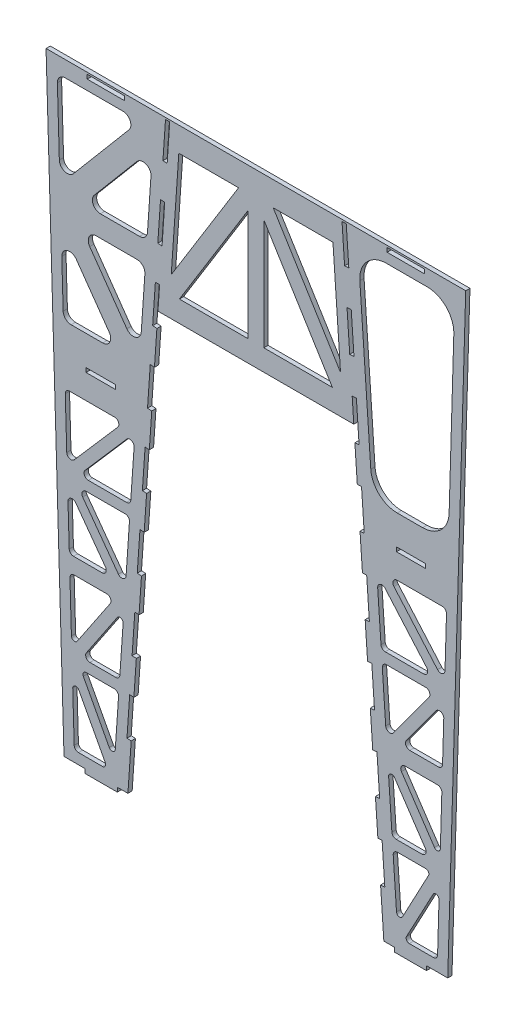
SolidWorks part; units mm, degrees
ref_plane "Front Plane" through (0, 0, 0) normal (0, 0, 1) x (1, 0, 0)
ref_plane "Top Plane" through (0, 0, 0) normal (0, 1, 0) x (1, 0, 0)
ref_plane "Right Plane" through (0, 0, 0) normal (1, 0, 0) x (0, 0, -1)
sketch "Sketch1" plane through (0, 0, 0) normal (0, 0, 1) x (1, 0, 0)
  line L0 (-288.2759, 0) -> (288.2759, 0) construction
  line L1 (-215.8925, 1465.1633) -> (215.8925, 1465.1633)
  line L2 (0, 0) -> (0, 1733.4513) construction
  line L3 (19.05, 1104.9) -> (205.6376, 1104.9)
  line L4 (202.8026, 1145.716) -> (41.4459, 1406.7433)
  line L5 (205.6376, 1104.9) -> (19.05, 1406.7433) construction
  line L6 (205.6376, 1104.9) -> (184.6725, 1406.7433)
  line L7 (183.2417, 1104.9) -> (15.2162, 1376.7154)
  line L8 (19.05, 1406.7433) -> (19.05, 1104.9)
  line L9 (184.6725, 1406.7433) -> (19.05, 1406.7433)
  line L10 (306.6278, 17.4764) -> (234.6272, 1054.1)
  line L12 (459.7218, 17.4764) -> (502.7833, 1465.1633)
  line L13 (459.7218, 7.3164) -> (520.3601, 2060.228) construction
  line L15 (266.6925, 1465.1633) -> (368.5375, 1465.1633)
  line L16 (-237.2124, 1016.8799) -> (-230.6925, 1110.7494) construction
  line L18 (237.2124, 1016.8799) -> (230.6925, 1110.7494) construction
  line L19 (-408.9218, 7.3164) -> (-332.1008, 7.3164)
  line L20 (-502.7833, 1465.1633) -> (-215.8925, 1465.1633)
  line L22 (408.9218, 7.3164) -> (332.7218, 7.3164)
  line L24 (-408.9218, 17.4764) -> (-408.9218, 7.3164) construction
  line L30 (-408.9218, 17.4764) -> (-408.9218, 7.3164)
  line L31 (502.7833, 1465.1633) -> (368.5375, 1465.1633)
  line L32 (-332.1008, 17.4764) -> (-332.1008, 7.3164) construction
  line L33 (-332.1008, 17.4764) -> (-332.1008, 7.3164)
  line L34 (408.9218, 17.4764) -> (408.9218, 7.3164) construction
  line L35 (408.9218, 17.4764) -> (408.9218, 7.3164)
  line L40 (332.7218, 17.4764) -> (332.7218, 7.3164) construction
  line L43 (332.7218, 17.4764) -> (332.7218, 7.3164)
  line L44 (459.7218, 17.4764) -> (408.9218, 17.4764) construction
  line L45 (459.7218, 17.4764) -> (408.9218, 17.4764)
  line L49 (-408.9218, 17.4764) -> (-459.7218, 17.4764)
  line L52 (-332.1008, 17.4764) -> (-306.6278, 17.4764)
  line L53 (332.7218, 17.4764) -> (306.6278, 17.4764)
  line L55 (-459.7218, 17.4764) -> (-502.7833, 1465.1633)
  line L56 (-459.7218, 7.3164) -> (-520.3601, 2060.228) construction
  line L81 (215.8925, 1465.1633) -> (266.6925, 1465.1633)
  line L90 (234.6272, 1054.1) -> (-234.6272, 1054.1)
  line L100 (-234.6272, 1054.1) -> (-306.6278, 17.4764)
  line L124 (-184.6725, 1406.7433) -> (-19.05, 1406.7433)
  line L125 (-19.05, 1406.7433) -> (-19.05, 1104.9)
  line L126 (-183.2417, 1104.9) -> (-15.2162, 1376.7154)
  line L127 (-205.6376, 1104.9) -> (-19.05, 1406.7433) construction
  line L128 (-202.8026, 1145.716) -> (-41.4459, 1406.7433)
  line L129 (-205.6376, 1104.9) -> (-184.6725, 1406.7433)
  line L130 (-19.05, 1104.9) -> (-205.6376, 1104.9)
  point P0 (0, 0)
  point P3 (0, 0)
  point P106 (0, 0)
  point P118 (0, 1054.1)
  dimension "D6" = 25.4
  dimension "D7" = 50.8
  dimension "D8" = 58.42
  dimension "D9" = 19.05
  dimension "D19" = 288.2759
  dimension "D22" = 19.05
  dimension "D23" = 19.05
  dimension "D24" = 1054.1
  dimension "D49" = 50.8
extrude "Boss-Extrude1" add sketch "Sketch1" along normal blind 10.16
fillet "Fillet1" [suppressed] radius 19.05
sketch "Sketch2" plane through (0, 0, 0) normal (0, 0, 1) x (1, 0, 0)
  line L18 (-222.6942, 1372.2749) -> (-212.5765, 1371.5721) construction
  line L56 (-216.5353, 1460.9479) -> (-222.6942, 1372.2749) construction
  line L57 (-212.5765, 1371.5721) -> (-206.3688, 1460.9479) construction
  line L58 (-206.3688, 1460.9479) -> (-216.5353, 1460.9479) construction
  line L59 (-222.6942, 1372.2749) -> (-212.5765, 1371.5721)
  line L61 (-216.5353, 1460.9479) -> (-222.6942, 1372.2749)
  line L63 (-212.5765, 1371.5721) -> (-206.3688, 1460.9479)
  line L176 (-206.3688, 1460.9479) -> (-216.5353, 1460.9479)
  line L181 (-224.8945, 1194.226) -> (-235.0121, 1194.9287) construction
  line L194 (-224.8945, 1194.226) -> (-218.3727, 1288.1221) construction
  line L199 (-218.3727, 1288.1221) -> (-228.4904, 1288.8248) construction
  line L208 (-228.4904, 1288.8248) -> (-235.0121, 1194.9287) construction
  line L213 (-224.8945, 1194.226) -> (-235.0121, 1194.9287)
  line L330 (-224.8945, 1194.226) -> (-218.3727, 1288.1221)
  line L331 (-218.3727, 1288.1221) -> (-228.4904, 1288.8248)
  line L332 (-228.4904, 1288.8248) -> (-235.0121, 1194.9287)
  line L333 (224.8945, 1194.226) -> (235.0121, 1194.9287) construction
  line L334 (235.0121, 1194.9287) -> (228.4904, 1288.8248) construction
  line L335 (218.3727, 1288.1221) -> (224.8945, 1194.226) construction
  line L336 (228.4904, 1288.8248) -> (218.3727, 1288.1221) construction
  line L337 (212.5765, 1371.5721) -> (222.6942, 1372.2749) construction
  line L338 (206.3688, 1460.9479) -> (212.5765, 1371.5721) construction
  line L339 (216.5353, 1460.9479) -> (206.3688, 1460.9479) construction
  line L340 (222.6942, 1372.2749) -> (216.5353, 1460.9479) construction
  line L341 (224.8945, 1194.226) -> (235.0121, 1194.9287)
  line L342 (235.0121, 1194.9287) -> (228.4904, 1288.8248)
  line L343 (218.3727, 1288.1221) -> (224.8945, 1194.226)
  line L344 (228.4904, 1288.8248) -> (218.3727, 1288.1221)
  line L345 (212.5765, 1371.5721) -> (222.6942, 1372.2749)
  line L346 (206.3688, 1460.9479) -> (212.5765, 1371.5721)
  line L347 (216.5353, 1460.9479) -> (206.3688, 1460.9479)
  line L348 (222.6942, 1372.2749) -> (216.5353, 1460.9479)
  line L349 (-240.8102, 1111.4521) -> (-247.33, 1017.5826) construction
  line L350 (-247.33, 1017.5826) -> (-237.2124, 1016.8799) construction
  line L351 (-230.6925, 1110.7494) -> (-240.8102, 1111.4521) construction
  line L353 (-240.8102, 1111.4521) -> (-247.33, 1017.5826)
  line L354 (-247.33, 1017.5826) -> (-237.2124, 1016.8799)
  line L355 (-230.6925, 1110.7494) -> (-240.8102, 1111.4521)
  line L357 (237.2124, 1016.8799) -> (247.33, 1017.5826) construction
  line L358 (247.33, 1017.5826) -> (240.8102, 1111.4521) construction
  line L360 (240.8102, 1111.4521) -> (230.6925, 1110.7494) construction
  line L361 (237.2124, 1016.8799) -> (247.33, 1017.5826)
  line L362 (247.33, 1017.5826) -> (240.8102, 1111.4521)
  line L364 (240.8102, 1111.4521) -> (230.6925, 1110.7494)
  line L365 (-306.6278, 17.4764) -> (-234.6272, 1054.1)
  line L366 (-234.6272, 1054.1) -> (234.6272, 1054.1)
  line L367 (234.6272, 1054.1) -> (306.6278, 17.4764)
  line L372 (408.9218, 17.4764) -> (459.7218, 17.4764)
  line L373 (459.7218, 17.4764) -> (502.7833, 1465.1633)
  line L374 (502.7833, 1465.1633) -> (-502.7833, 1465.1633)
  line L375 (-502.7833, 1465.1633) -> (-459.7218, 17.4764)
  line L376 (-459.7218, 17.4764) -> (-408.9218, 17.4764)
  line L377 (-408.9218, 17.4764) -> (-408.9218, 7.3164)
  line L378 (-408.9218, 7.3164) -> (-332.1008, 7.3164)
  line L379 (-332.1008, 7.3164) -> (-332.1008, 17.4764)
  line L380 (-332.1008, 17.4764) -> (-306.6278, 17.4764)
  line L381 (-298.8019, 130.1492) -> (-292.2913, 223.886)
  line L405 (-243.0122, 933.3767) -> (-253.1299, 934.0795) construction
  line L406 (-253.1299, 934.0795) -> (-259.648, 840.2365) construction
  line L407 (-249.5303, 839.5337) -> (-259.648, 840.2365) construction
  line L408 (-243.0122, 933.3767) -> (-253.1299, 934.0795)
  line L417 (-253.1299, 934.0795) -> (-259.648, 840.2365)
  line L418 (-249.5303, 839.5337) -> (-259.648, 840.2365)
  line L419 (243.0122, 933.3767) -> (253.1299, 934.0795) construction
  line L420 (253.1299, 934.0795) -> (259.648, 840.2365) construction
  line L421 (249.5303, 839.5337) -> (259.648, 840.2365) construction
  line L422 (243.0122, 933.3767) -> (253.1299, 934.0795)
  line L423 (253.1299, 934.0795) -> (259.648, 840.2365)
  line L424 (249.5303, 839.5337) -> (259.648, 840.2365)
  line L425 (-267.6517, 578.6314) -> (-277.7694, 579.3341) construction
  line L426 (-255.332, 756.0041) -> (-265.4497, 756.7068) construction
  line L427 (-265.4497, 756.7068) -> (-271.9659, 662.8903) construction
  line L428 (-261.8482, 662.1876) -> (-271.9659, 662.8903) construction
  line L429 (-277.7694, 579.3341) -> (-284.2838, 485.5442) construction
  line L430 (-274.1661, 484.8415) -> (-284.2838, 485.5442) construction
  line L431 (-274.1661, 484.8415) -> (-284.2838, 485.5442)
  line L432 (-277.7694, 579.3341) -> (-284.2838, 485.5442)
  line L433 (-267.6517, 578.6314) -> (-277.7694, 579.3341)
  line L434 (-261.8482, 662.1876) -> (-271.9659, 662.8903)
  line L435 (-265.4497, 756.7068) -> (-271.9659, 662.8903)
  line L436 (-255.332, 756.0041) -> (-265.4497, 756.7068)
  line L437 (261.8482, 662.1876) -> (271.9659, 662.8903) construction
  line L438 (255.332, 756.0041) -> (265.4497, 756.7068) construction
  line L439 (265.4497, 756.7068) -> (271.9659, 662.8903) construction
  line L440 (261.8482, 662.1876) -> (271.9659, 662.8903)
  line L449 (255.332, 756.0041) -> (265.4497, 756.7068)
  line L450 (265.4497, 756.7068) -> (271.9659, 662.8903)
  line L451 (274.1661, 484.8415) -> (284.2838, 485.5442) construction
  line L452 (277.7694, 579.3341) -> (284.2838, 485.5442) construction
  line L453 (267.6517, 578.6314) -> (277.7694, 579.3341) construction
  line L454 (274.1661, 484.8415) -> (284.2838, 485.5442)
  line L455 (277.7694, 579.3341) -> (284.2838, 485.5442)
  line L456 (267.6517, 578.6314) -> (277.7694, 579.3341)
  line L457 (-298.8019, 130.1492) -> (-308.9196, 130.8519) construction
  line L458 (-302.4089, 224.5888) -> (-308.9196, 130.8519) construction
  line L459 (-292.2913, 223.886) -> (-302.4089, 224.5888) construction
  line L460 (-286.484, 307.4953) -> (-296.6017, 308.1981) construction
  line L461 (-290.0892, 401.9615) -> (-296.6017, 308.1981) construction
  line L462 (-279.9715, 401.2587) -> (-290.0892, 401.9615) construction
  line L463 (-298.8019, 130.1492) -> (-308.9196, 130.8519)
  line L464 (-302.4089, 224.5888) -> (-308.9196, 130.8519)
  line L465 (-292.2913, 223.886) -> (-302.4089, 224.5888)
  line L466 (-286.484, 307.4953) -> (-296.6017, 308.1981)
  line L467 (-290.0892, 401.9615) -> (-296.6017, 308.1981)
  line L468 (-279.9715, 401.2587) -> (-290.0892, 401.9615)
  line L469 (286.484, 307.4953) -> (296.6017, 308.1981) construction
  line L470 (279.9715, 401.2587) -> (290.0892, 401.9615) construction
  line L471 (290.0892, 401.9615) -> (296.6017, 308.1981) construction
  line L472 (286.484, 307.4953) -> (296.6017, 308.1981)
  line L473 (279.9715, 401.2587) -> (290.0892, 401.9615)
  line L474 (290.0892, 401.9615) -> (296.6017, 308.1981)
  line L475 (298.8019, 130.1492) -> (308.9196, 130.8519) construction
  line L476 (302.4089, 224.5888) -> (308.9196, 130.8519) construction
  line L477 (292.2913, 223.886) -> (302.4089, 224.5888) construction
  line L478 (298.8019, 130.1492) -> (308.9196, 130.8519)
  line L479 (302.4089, 224.5888) -> (308.9196, 130.8519)
  line L480 (292.2913, 223.886) -> (302.4089, 224.5888)
  line L481 (-230.6925, 1110.7494) -> (-237.2124, 1016.8799)
  line L482 (243.0122, 933.3767) -> (249.5303, 839.5337)
  line L483 (255.332, 756.0041) -> (261.8482, 662.1876)
  line L484 (-249.5303, 839.5337) -> (-243.0122, 933.3767)
  line L485 (-261.8482, 662.1876) -> (-255.332, 756.0041)
  line L486 (267.6517, 578.6314) -> (274.1661, 484.8415)
  line L487 (-286.484, 307.4953) -> (-279.9715, 401.2587)
  line L488 (-274.1661, 484.8415) -> (-267.6517, 578.6314)
  line L489 (279.9715, 401.2587) -> (286.484, 307.4953)
  line L490 (292.2913, 223.886) -> (298.8019, 130.1492)
  line L492 (230.6925, 1110.7494) -> (237.2124, 1016.8799)
  line L499 (306.6278, 17.4764) -> (332.7218, 17.4764)
  line L500 (332.7218, 17.4764) -> (332.7218, 7.3164)
  line L501 (332.7218, 7.3164) -> (408.9218, 7.3164)
  line L502 (408.9218, 7.3164) -> (408.9218, 17.4764)
  dimension "D1" = 0
extrude "Cut-Extrude5" cut sketch "Sketch2" along normal blind 12.7
sketch "Sketch4" plane through (0, 0, 10.16) normal (0, 0, 1) x (1, 0, 0)
  line L0 (404.4148, 1450.7879) -> (404.4148, 1460.9479) construction
  line L1 (314.4148, 1450.7879) -> (404.4148, 1450.7879) construction
  line L2 (314.4148, 1450.7879) -> (314.4148, 1460.9479) construction
  line L3 (404.4148, 1460.9479) -> (314.4148, 1460.9479) construction
  line L4 (404.4148, 1450.7879) -> (404.4148, 1460.9479)
  line L5 (314.4148, 1450.7879) -> (404.4148, 1450.7879)
  line L6 (314.4148, 1450.7879) -> (314.4148, 1460.9479)
  line L7 (404.4148, 1460.9479) -> (314.4148, 1460.9479)
  line L8 (336.9598, 840.6279) -> (336.9598, 850.7879) construction
  line L9 (336.9598, 840.6279) -> (406.9598, 840.6279) construction
  line L10 (406.9598, 840.6279) -> (406.9598, 850.7879) construction
  line L11 (406.9598, 850.7879) -> (336.9598, 850.7879) construction
  line L12 (336.9598, 840.6279) -> (336.9598, 850.7879)
  line L13 (336.9598, 840.6279) -> (406.9598, 840.6279)
  line L14 (406.9598, 840.6279) -> (406.9598, 850.7879)
  line L15 (406.9598, 850.7879) -> (336.9598, 850.7879)
extrude "Cut-Extrude6" cut sketch "Sketch4" against normal through all both
ref_plane "Plane1" through (0, 0, 0) normal (1, 0, 0) x (0, 0, -1)
mirror "Mirror1" about plane through (0, 0, 0) normal (1, 0, 0) of "Cut-Extrude6"
sketch "Sketch5" plane through (0, 0, 10.16) normal (0, 0, 1) x (1, 0, 0)
  line L0 (435.0661, 42.8764) -> (476.2387, 1427.0633)
  line L1 (476.2387, 1427.0633) -> (244.35, 1427.0633)
  line L2 (244.35, 1427.0633) -> (340.4913, 42.8764)
  line L3 (340.4913, 42.8764) -> (435.0661, 42.8764)
  line L4 (281.2007, 896.5079) -> (460.4574, 896.5079)
  line L5 (457.4353, 794.9079) -> (288.2575, 794.9079)
  line L6 (336.9598, 840.6279) -> (406.9598, 840.6279) construction
  line L7 (476.2387, 1427.0633) -> (460.4574, 896.5079)
  line L8 (468.3481, 1161.7856) -> (281.2007, 896.5079) construction
  line L9 (244.35, 1427.0633) -> (468.3481, 1161.7856) construction
  line L10 (244.35, 1427.0633) -> (281.2007, 896.5079)
  line L11 (281.2007, 896.5079) -> (244.35, 1427.0633)
  line L12 (262.7753, 1161.7856) -> (468.3481, 1161.7856) construction
  line L13 (435.0661, 42.8764) -> (457.4353, 794.9079)
  line L14 (446.2507, 418.8922) -> (457.4353, 794.9079)
  line L15 (451.843, 606.9001) -> (288.2575, 794.9079) construction
  line L16 (451.843, 606.9001) -> (314.3744, 418.8922) construction
  line L17 (446.2507, 418.8922) -> (435.0661, 42.8764)
  line L18 (440.6584, 230.8843) -> (314.3744, 418.8922) construction
  line L19 (440.6584, 230.8843) -> (340.4913, 42.8764) construction
  line L20 (451.843, 606.9001) -> (301.316, 606.9001) construction
  line L21 (314.3744, 418.8922) -> (446.2507, 418.8922) construction
  line L22 (440.6584, 230.8843) -> (327.4329, 230.8843) construction
  line L23 (354.8813, 42.8764) -> (439.8075, 202.2779)
  line L24 (338.8317, 66.7706) -> (419.502, 218.1843)
  line L25 (328.315, 218.1843) -> (419.502, 218.1843)
  line L26 (326.5508, 243.5843) -> (416.8288, 243.5843)
  line L27 (416.8288, 243.5843) -> (316.1389, 393.4886)
  line L28 (441.3071, 252.6951) -> (338.204, 406.1922)
  line L29 (338.204, 406.1922) -> (445.8729, 406.1922)
  line L30 (447.0062, 444.2922) -> (348.6793, 444.2922)
  line L31 (348.6793, 444.2922) -> (451.1758, 584.4708)
  line L32 (313.0096, 438.5424) -> (426.8241, 594.2001)
  line L33 (426.8241, 594.2001) -> (302.1981, 594.2001)
  line L34 (300.4339, 619.6001) -> (423.9583, 619.6001)
  line L35 (423.9583, 619.6001) -> (289.7179, 773.8818)
  line L36 (452.3994, 625.6082) -> (316.1422, 782.2079)
  line L37 (316.1422, 782.2079) -> (457.0575, 782.2079)
  line L38 (277.5939, 1427.0633) -> (469.4793, 1199.8162)
  line L39 (247.3296, 1384.1643) -> (413.6566, 1187.1856)
  line L40 (413.6566, 1187.1856) -> (261.0111, 1187.1856)
  line L41 (264.5396, 1136.3856) -> (419.3443, 1136.3856)
  line L42 (419.3443, 1136.3856) -> (278.4146, 936.6206)
  line L43 (466.9797, 1115.7842) -> (330.2045, 921.9079)
  line L44 (330.2045, 921.9079) -> (461.2129, 921.9079)
  line L64 (-234.6272, 1054.1) -> (234.6272, 1054.1)
  line L65 (234.6272, 1054.1) -> (230.6925, 1110.7494)
  line L66 (230.6925, 1110.7494) -> (240.8102, 1111.4521)
  line L67 (240.8102, 1111.4521) -> (247.33, 1017.5826)
  line L68 (247.33, 1017.5826) -> (237.2124, 1016.8799)
  line L69 (237.2124, 1016.8799) -> (243.0122, 933.3767)
  line L70 (243.0122, 933.3767) -> (253.1299, 934.0795)
  line L71 (253.1299, 934.0795) -> (259.648, 840.2365)
  line L72 (259.648, 840.2365) -> (249.5303, 839.5337)
  line L73 (249.5303, 839.5337) -> (255.332, 756.0041)
  line L74 (255.332, 756.0041) -> (265.4497, 756.7068)
  line L75 (265.4497, 756.7068) -> (271.9659, 662.8903)
  line L76 (271.9659, 662.8903) -> (261.8482, 662.1876)
  line L77 (261.8482, 662.1876) -> (267.6517, 578.6314)
  line L78 (267.6517, 578.6314) -> (277.7694, 579.3341)
  line L79 (277.7694, 579.3341) -> (284.2838, 485.5442)
  line L80 (284.2838, 485.5442) -> (274.1661, 484.8415)
  line L81 (274.1661, 484.8415) -> (279.9715, 401.2587)
  line L82 (279.9715, 401.2587) -> (290.0892, 401.9615)
  line L83 (290.0892, 401.9615) -> (296.6017, 308.1981)
  line L84 (296.6017, 308.1981) -> (286.484, 307.4953)
  line L85 (286.484, 307.4953) -> (292.2913, 223.886)
  line L86 (292.2913, 223.886) -> (302.4089, 224.5888)
  line L87 (302.4089, 224.5888) -> (308.9196, 130.8519)
  line L88 (308.9196, 130.8519) -> (298.8019, 130.1492)
  line L89 (298.8019, 130.1492) -> (306.6278, 17.4764)
  line L90 (306.6278, 17.4764) -> (332.7218, 17.4764)
  line L91 (332.7218, 17.4764) -> (332.7218, 7.3164)
  line L92 (332.7218, 7.3164) -> (408.9218, 7.3164)
  line L93 (408.9218, 7.3164) -> (408.9218, 17.4764)
  line L94 (408.9218, 17.4764) -> (459.7218, 17.4764)
  line L95 (459.7218, 17.4764) -> (502.7833, 1465.1633)
  line L96 (502.7833, 1465.1633) -> (-502.7833, 1465.1633)
  line L97 (-502.7833, 1465.1633) -> (-459.7218, 17.4764)
  line L98 (-459.7218, 17.4764) -> (-408.9218, 17.4764)
  line L99 (-408.9218, 17.4764) -> (-408.9218, 7.3164)
  line L100 (-408.9218, 7.3164) -> (-332.1008, 7.3164)
  line L101 (-332.1008, 7.3164) -> (-332.1008, 17.4764)
  line L102 (-332.1008, 17.4764) -> (-306.6278, 17.4764)
  line L103 (-306.6278, 17.4764) -> (-298.8019, 130.1492)
  line L104 (-298.8019, 130.1492) -> (-308.9196, 130.8519)
  line L105 (-308.9196, 130.8519) -> (-302.4089, 224.5888)
  line L106 (-302.4089, 224.5888) -> (-292.2913, 223.886)
  line L107 (-292.2913, 223.886) -> (-286.484, 307.4953)
  line L108 (-286.484, 307.4953) -> (-296.6017, 308.1981)
  line L109 (-296.6017, 308.1981) -> (-290.0892, 401.9615)
  line L110 (-290.0892, 401.9615) -> (-279.9715, 401.2587)
  line L111 (-279.9715, 401.2587) -> (-274.1661, 484.8415)
  line L112 (-274.1661, 484.8415) -> (-284.2838, 485.5442)
  line L113 (-284.2838, 485.5442) -> (-277.7694, 579.3341)
  line L114 (-277.7694, 579.3341) -> (-267.6517, 578.6314)
  line L115 (-267.6517, 578.6314) -> (-261.8482, 662.1876)
  line L116 (-261.8482, 662.1876) -> (-271.9659, 662.8903)
  line L117 (-271.9659, 662.8903) -> (-265.4497, 756.7068)
  line L118 (-265.4497, 756.7068) -> (-255.332, 756.0041)
  line L119 (-255.332, 756.0041) -> (-249.5303, 839.5337)
  line L120 (-249.5303, 839.5337) -> (-259.648, 840.2365)
  line L121 (-259.648, 840.2365) -> (-253.1299, 934.0795)
  line L122 (-253.1299, 934.0795) -> (-243.0122, 933.3767)
  line L123 (-243.0122, 933.3767) -> (-237.2124, 1016.8799)
  line L124 (-237.2124, 1016.8799) -> (-247.33, 1017.5826)
  line L125 (-247.33, 1017.5826) -> (-240.8102, 1111.4521)
  line L126 (-240.8102, 1111.4521) -> (-230.6925, 1110.7494)
  line L127 (-230.6925, 1110.7494) -> (-234.6272, 1054.1)
  line L128 (-234.6272, 1054.1) -> (234.6272, 1054.1)
  line L129 (234.6272, 1054.1) -> (230.6925, 1110.7494)
  line L130 (230.6925, 1110.7494) -> (240.8102, 1111.4521)
  line L131 (240.8102, 1111.4521) -> (247.33, 1017.5826)
  line L132 (247.33, 1017.5826) -> (237.2124, 1016.8799)
  line L133 (237.2124, 1016.8799) -> (243.0122, 933.3767)
  line L134 (243.0122, 933.3767) -> (253.1299, 934.0795)
  line L135 (253.1299, 934.0795) -> (259.648, 840.2365)
  line L136 (259.648, 840.2365) -> (249.5303, 839.5337)
  line L137 (249.5303, 839.5337) -> (255.332, 756.0041)
  line L138 (255.332, 756.0041) -> (265.4497, 756.7068)
  line L139 (265.4497, 756.7068) -> (271.9659, 662.8903)
  line L140 (271.9659, 662.8903) -> (261.8482, 662.1876)
  line L141 (261.8482, 662.1876) -> (267.6517, 578.6314)
  line L142 (267.6517, 578.6314) -> (277.7694, 579.3341)
  line L143 (277.7694, 579.3341) -> (284.2838, 485.5442)
  line L144 (284.2838, 485.5442) -> (274.1661, 484.8415)
  line L145 (274.1661, 484.8415) -> (279.9715, 401.2587)
  line L146 (279.9715, 401.2587) -> (290.0892, 401.9615)
  line L147 (290.0892, 401.9615) -> (296.6017, 308.1981)
  line L148 (296.6017, 308.1981) -> (286.484, 307.4953)
  line L149 (286.484, 307.4953) -> (292.2913, 223.886)
  line L150 (292.2913, 223.886) -> (302.4089, 224.5888)
  line L151 (302.4089, 224.5888) -> (308.9196, 130.8519)
  line L152 (308.9196, 130.8519) -> (298.8019, 130.1492)
  line L153 (298.8019, 130.1492) -> (306.6278, 17.4764)
  line L154 (306.6278, 17.4764) -> (332.7218, 17.4764)
  line L155 (332.7218, 17.4764) -> (332.7218, 7.3164)
  line L156 (332.7218, 7.3164) -> (408.9218, 7.3164)
  line L157 (408.9218, 7.3164) -> (408.9218, 17.4764)
  line L158 (408.9218, 17.4764) -> (459.7218, 17.4764)
  line L159 (459.7218, 17.4764) -> (502.7833, 1465.1633)
  line L160 (502.7833, 1465.1633) -> (-502.7833, 1465.1633)
  line L161 (-502.7833, 1465.1633) -> (-459.7218, 17.4764)
  line L162 (-459.7218, 17.4764) -> (-408.9218, 17.4764)
  line L163 (-408.9218, 17.4764) -> (-408.9218, 7.3164)
  line L164 (-408.9218, 7.3164) -> (-332.1008, 7.3164)
  line L165 (-332.1008, 7.3164) -> (-332.1008, 17.4764)
  line L166 (-332.1008, 17.4764) -> (-306.6278, 17.4764)
  line L167 (-306.6278, 17.4764) -> (-298.8019, 130.1492)
  line L168 (-298.8019, 130.1492) -> (-308.9196, 130.8519)
  line L169 (-308.9196, 130.8519) -> (-302.4089, 224.5888)
  line L170 (-302.4089, 224.5888) -> (-292.2913, 223.886)
  line L171 (-292.2913, 223.886) -> (-286.484, 307.4953)
  line L172 (-286.484, 307.4953) -> (-296.6017, 308.1981)
  line L173 (-296.6017, 308.1981) -> (-290.0892, 401.9615)
  line L174 (-290.0892, 401.9615) -> (-279.9715, 401.2587)
  line L175 (-279.9715, 401.2587) -> (-274.1661, 484.8415)
  line L176 (-274.1661, 484.8415) -> (-284.2838, 485.5442)
  line L177 (-284.2838, 485.5442) -> (-277.7694, 579.3341)
  line L178 (-277.7694, 579.3341) -> (-267.6517, 578.6314)
  line L179 (-267.6517, 578.6314) -> (-261.8482, 662.1876)
  line L180 (-261.8482, 662.1876) -> (-271.9659, 662.8903)
  line L181 (-271.9659, 662.8903) -> (-265.4497, 756.7068)
  line L182 (-265.4497, 756.7068) -> (-255.332, 756.0041)
  line L183 (-255.332, 756.0041) -> (-249.5303, 839.5337)
  line L184 (-249.5303, 839.5337) -> (-259.648, 840.2365)
  line L185 (-259.648, 840.2365) -> (-253.1299, 934.0795)
  line L186 (-253.1299, 934.0795) -> (-243.0122, 933.3767)
  line L187 (-243.0122, 933.3767) -> (-237.2124, 1016.8799)
  line L188 (-237.2124, 1016.8799) -> (-247.33, 1017.5826)
  line L189 (-247.33, 1017.5826) -> (-240.8102, 1111.4521)
  line L190 (-240.8102, 1111.4521) -> (-230.6925, 1110.7494)
  line L191 (-230.6925, 1110.7494) -> (-234.6272, 1054.1)
  point P104 (0, 0)
  point P108 (0, 0)
  point P110 (290.0892, 734.9698)
  point P112 (0, 0)
  point P114 (0, 0)
  dimension "D2" = 38.1
  dimension "D3" = 25.4
  dimension "D4" = 25.4
  dimension "D5" = 25.4
  dimension "D6" = 101.6
  dimension "D7" = 45.72
  dimension "D8" = 12.7
  dimension "D9" = 12.7
  dimension "D10" = 12.7
  dimension "D11" = 12.7
  dimension "D12" = 12.7
  dimension "D13" = 12.7
  dimension "D14" = 12.7
  dimension "D15" = 25.4
  dimension "D16" = 12.7
  dimension "D17" = 12.7
  dimension "D18" = 12.7
  dimension "D19" = 12.7
  dimension "D20" = 12.7
  dimension "D21" = 12.7
  dimension "D22" = 12.7
  dimension "D23" = 25.4
  dimension "D24" = 25.4
  dimension "D25" = 25.4
  dimension "D26" = 25.4
  dimension "D27" = 25.4
  dimension "D28" = 25.4
  dimension "D29" = 25.4
  dimension "D1" = 0
extrude "Cut-Extrude7" cut sketch "Sketch5" against normal through all both contours L1 L38 L7 | L40 L39 L11 | L42 L41 L11 | L43 L44 L7 | L37 L36 L14 | L34 L35 L2 | L32 L33 L2 | L31 L30 L14 | L29 L28 L0 | L26 L27 L2 | L25 L2 L24 | L23 L3 L0
fillet "Fillet3" radius 10.16 18 edges at (423.9583, 619.6001, 5.08) (300.4339, 619.6001, 5.08) (289.7179, 773.8818, 5.08) (426.8241, 594.2001, 5.08) (313.0096, 438.5424, 5.08) (302.1981, 594.2001, 5.08) (348.6793, 444.2922, 5.08) (451.1758, 584.4708, 5.08) (447.0062, 444.2922, 5.08) (338.204, 406.1922, 5.08) (445.8729, 406.1922, 5.08) (316.1422, 782.2079, 5.08) (457.0575, 782.2079, 5.08) (452.3994, 625.6082, 5.08) (435.0661, 42.8764, 5.08) (328.315, 218.1843, 5.08) (416.8288, 243.5843, 5.08) (326.5508, 243.5843, 5.08)
fillet "Fillet4" radius 7.62 6 edges at (441.3071, 252.6951, 5.08) (354.8813, 42.8764, 5.08) (439.8075, 202.2779, 5.08) (419.502, 218.1843, 5.08) (338.8317, 66.7706, 5.08) (316.1389, 393.4886, 5.08)
fillet "Fillet5" radius 19.05 12 edges at (330.2045, 921.9079, 5.08) (461.2129, 921.9079, 5.08) (419.3443, 1136.3856, 5.08) (466.9797, 1115.7842, 5.08) (476.2387, 1427.0633, 5.08) (469.4793, 1199.8162, 5.08) (413.6566, 1187.1856, 5.08) (277.5939, 1427.0633, 5.08) (247.3296, 1384.1643, 5.08) (264.5396, 1136.3856, 5.08) (261.0111, 1187.1856, 5.08) (278.4146, 936.6206, 5.08)
mirror "Mirror2" about plane through (0, 0, 0) normal (1, 0, 0) of "Cut-Extrude7", "Fillet3", "Fillet4", "Fillet5"
sketch "Sketch6" plane through (0, 0, 10.16) normal (0, 0, 1) x (1, 0, 0)
  line L0 (244.35, 1427.0633) -> (279.4365, 921.9079)
  line L1 (279.4365, 921.9079) -> (461.2129, 921.9079)
  line L2 (461.2129, 921.9079) -> (476.2387, 1427.0633)
  line L3 (366.9573, 921.9079) -> (442.7211, 921.9079) construction
  line L4 (244.35, 1427.0633) -> (476.2387, 1427.0633)
  line L5 (470.9594, 1249.5753) -> (475.6553, 1407.4469) construction
  line L6 (251.3676, 1326.0281) -> (259.7797, 1204.9157) construction
  line L7 (456.6137, 1427.0633) -> (318.6124, 1427.0633) construction
extrude "Cut-Extrude8" cut sketch "Sketch6" against normal through all both
fillet "Fillet6" radius 63.5 4 edges at (476.2387, 1427.0633, 5.08) (461.2129, 921.9079, 5.08) (279.4365, 921.9079, 5.08) (244.35, 1427.0633, 5.08)
